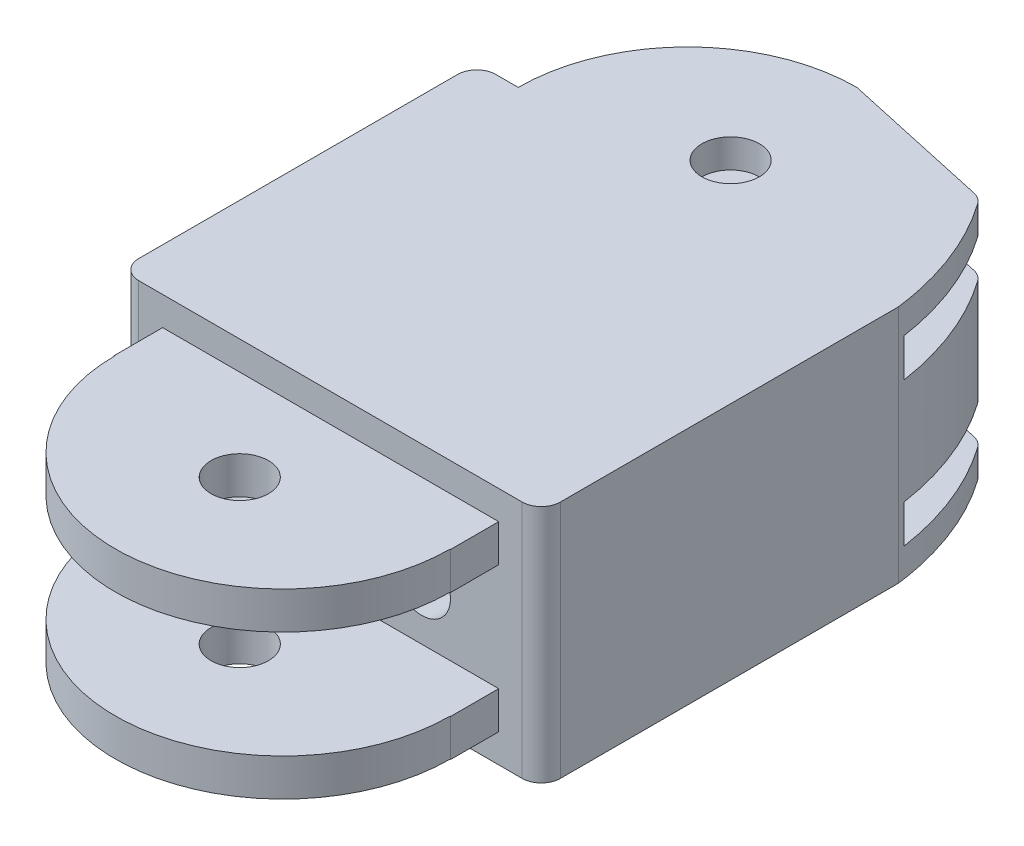
SolidWorks part; units mm, degrees
ref_plane "Front Plane" through (0, 0, 0) normal (0, 0, 1) x (1, 0, 0)
ref_plane "Top Plane" through (0, 0, 0) normal (0, 1, 0) x (1, 0, 0)
ref_plane "Right Plane" through (0, 0, 0) normal (1, 0, 0) x (0, 0, -1)
sketch "Sketch2" plane through (0, 0, 0) normal (0, 0, 1) x (1, 0, 0)
  line L0 (-24.2561, -24.0702) -> (-22.0061, -24.0702) construction
  line L1 (-24.2561, -17.8202) -> (-2.2017, -17.8202) construction
  line L2 (-24.2561, -17.8202) -> (-24.2561, -30.3202) construction
  line L3 (-24.2561, -30.3202) -> (-2.2017, -30.3202) construction
  line L4 (-2.2017, -17.8202) -> (-2.2017, -30.3202) construction
  line L5 (-2.2017, -24.0702) -> (-4.4517, -24.0702) construction
  line L6 (-22.0061, -24.0702) -> (-22.0061, -30.3202) construction
  line L7 (-4.4517, -24.0702) -> (-4.4517, -30.3202) construction
  line L8 (-24.2561, -17.8202) -> (-24.2561, -19.3148) construction
  line L9 (-24.2561, -19.3148) -> (-22.0061, -19.3148) construction
  line L10 (-2.2017, -17.8202) -> (-2.2017, -19.3148) construction
  line L11 (-2.2017, -19.3148) -> (-4.4517, -19.3148) construction
  line L12 (-2.2017, -30.3202) -> (-2.2017, -28.8202) construction
  line L13 (-2.2017, -28.8202) -> (-4.4517, -28.8202) construction
  line L14 (-24.2561, -30.3202) -> (-24.2561, -28.8202) construction
  line L15 (-24.2561, -28.8202) -> (-22.0061, -28.8202) construction
  line L17 (-22.0061, -28.8202) -> (-4.4517, -28.8202)
  line L18 (-22.0061, -28.8202) -> (-22.0061, -26.8702)
  line L19 (-22.0061, -26.8702) -> (-4.4517, -26.8702)
  line L20 (-4.4517, -28.8202) -> (-4.4517, -26.8702)
  line L21 (-22.0061, -28.8202) -> (-4.4517, -26.8702) construction
  line L22 (-22.0061, -26.8702) -> (-4.4517, -28.8202) construction
  line L23 (-22.0061, -19.3148) -> (-4.4517, -19.3148)
  line L24 (-22.0061, -19.3148) -> (-22.0061, -21.2648)
  line L25 (-22.0061, -21.2648) -> (-4.4517, -21.2648)
  line L26 (-4.4517, -19.3148) -> (-4.4517, -21.2648)
  line L27 (-22.0061, -19.3148) -> (-4.4517, -21.2648) construction
  line L28 (-22.0061, -21.2648) -> (-4.4517, -19.3148) construction
  point P19 (-13.2289, -27.8452)
  point P22 (-13.2289, -20.2898)
extrude "Boss-Extrude1" add sketch "Sketch2" along normal blind 8.75
sketch "Sketch3" plane through (0, -19.3148, 0) normal (0, 1, 0) x (1, 0, 0)
  line L0 (-4.4517, 0) -> (-22.0061, 0) construction
  line L1 (-4.4517, -8.75) -> (-22.0061, -8.75) construction
  arc A0 (-13.2289, -8.75) -> (-4.4789, 0) centre (-13.2289, 0) ccw
  arc A1 (-13.2289, -8.75) -> (-21.9789, 0) centre (-13.2289, 0) cw
  spline S0 degree 2 poles (-22.0061, -8.75) (-13.2289, -12.4735) (-4.4517, -8.75) knots 0 0 0 1 1 1
  spline S1 degree 2 poles (-21.9789, 0) (-25.927, -4.2429) (-22.0061, -8.75) knots 0 0 0 1 1 1
  spline S2 degree 2 poles (-4.4789, 0) (1.1383, -4.1517) (-4.4517, -8.75) knots 0 0 0 1 1 1
extrude "Cut-Extrude1" cut sketch "Sketch3" against normal through all contours S0 S2 A0 A1 S1
sketch "Sketch4" plane through (0, 0, 0) normal (0, 0, -1) x (-1, 0, 0)
  line L0 (22.0061, -19.3148) -> (24.2561, -19.3148) construction
  line L1 (22.0061, -19.3148) -> (4.4789, -19.3148) construction
  line L2 (22.0061, -19.3148) -> (22.0061, -28.8202) construction
  line L3 (22.0061, -28.8202) -> (4.4789, -28.8202) construction
  line L4 (4.4789, -19.3148) -> (4.4789, -28.8202) construction
  line L5 (22.0061, -19.3148) -> (4.4789, -28.8202) construction
  line L6 (22.0061, -28.8202) -> (4.4789, -19.3148) construction
  line L7 (24.2561, -19.3148) -> (24.2561, -17.8148) construction
  line L8 (4.4789, -28.8202) -> (2.2289, -28.8202) construction
  line L9 (2.2289, -28.8202) -> (2.2289, -30.3202) construction
  line L11 (24.2561, -17.8148) -> (2.2289, -17.8148)
  line L12 (24.2561, -17.8148) -> (24.2561, -30.3202)
  line L13 (24.2561, -30.3202) -> (2.2289, -30.3202)
  line L14 (2.2289, -17.8148) -> (2.2289, -30.3202)
  line L15 (24.2561, -17.8148) -> (2.2289, -30.3202) construction
  line L16 (24.2561, -30.3202) -> (2.2289, -17.8148) construction
  point P4 (13.2425, -24.0675)
  point P7 (0, 0)
  point P14 (13.2425, -24.0675)
  point P15 (0, 0)
  point P16 (0, 0)
  point P17 (0, 0)
  point P18 (0, 0)
extrude "Boss-Extrude2" add sketch "Sketch4" along normal blind 30 contours L12 L13 L14 L11
sketch "Sketch5" plane through (0, -19.3148, 0) normal (0, 1, 0) x (1, 0, 0)
  line L0 (-13.2289, -8.75) -> (-13.2289, -2.25) construction
  arc A0 (-21.9789, 0) -> (-4.4789, 0) centre (-13.2289, 0) ccw construction
  circle A1 centre (-13.2289, -2.25) radius 1.5
extrude "Cut-Extrude2" cut sketch "Sketch5" against normal blind 12 contours A1
sketch "Sketch6" plane through (0, 0, 0) normal (0, 0, 1) x (1, 0, 0)
  line L0 (-24.2561, -30.3202) -> (-2.2289, -30.3202)
  line L1 (-2.2289, -30.3202) -> (-2.2289, -17.8148)
  line L2 (-2.2289, -17.8148) -> (-24.2561, -17.8148)
  line L3 (-24.2561, -17.8148) -> (-24.2561, -30.3202)
  line L4 (-22.0061, -28.8202) -> (-4.4517, -28.8202)
  line L5 (-4.4517, -28.8202) -> (-4.4517, -26.8702)
  line L6 (-4.4517, -28.8202) -> (-4.4517, -26.8702) construction
  line L7 (-4.4517, -26.8702) -> (-22.0061, -26.8702)
  line L8 (-22.0061, -28.8202) -> (-22.0061, -26.8702)
  line L9 (-22.0061, -21.2648) -> (-22.0061, -19.3148)
  line L10 (-22.0061, -19.3148) -> (-4.4517, -19.3148)
  line L11 (-4.4517, -19.3148) -> (-4.4517, -21.2648)
  line L12 (-4.4517, -21.2648) -> (-22.0061, -21.2648)
extrude "Cut-Extrude3" cut sketch "Sketch6" against normal blind 2.5
sketch "Sketch7" plane through (0, -17.8148, 0) normal (0, 1, 0) x (1, 0, 0)
  line L0 (-13.2425, 30) -> (-13.2425, 23.4057) construction
  line L1 (-24.2561, 30) -> (-2.2289, 30) construction
  line L2 (-13.2425, 23.4057) -> (-13.2425, 21.1557) construction
  line L3 (-22.0869, 21.1557) -> (-24.2561, 21.1557)
  line L4 (-24.2561, 30) -> (-24.2561, 2.5) construction
  line L6 (-2.2289, 30) -> (-2.2289, 2.5) construction
  line L7 (-13.2425, 30) -> (-5.0463, 28.2017)
  circle A0 centre (-13.2425, 23.4057) radius 1.5
  arc A1 (-13.2425, 30) -> (-22.0869, 21.1557) centre (-13.2425, 21.1557) ccw
  spline S0 degree 3 poles (-2.2289, 21.1557) (11.4715, 27.1897) (-11.7652, 53.4313) (-37.0079, 21.5236) (-24.2561, 21.1557) knots 0 0 0 0 0.520113 1 1 1 1
  spline S1 degree 2 poles (-5.0463, 28.2017) (-2.7315, 25.0686) (-2.2289, 21.1557) knots 0 0 0 1 1 1
extrude "Cut-Extrude4" cut sketch "Sketch7" against normal blind 13
sketch "Sketch8" plane through (0, 0, -2.5) normal (0, 0, 1) x (1, 0, 0)
  line L0 (-24.2561, -24.0675) -> (-18.0111, -24.0675) construction
  line L1 (-24.2561, -17.8148) -> (-24.2561, -30.3202) construction
  line L2 (-2.2289, -24.0675) -> (-8.474, -24.0675) construction
  line L3 (-2.2289, -30.3202) -> (-2.2289, -17.8148) construction
  line L4 (-4.4517, -21.2648) -> (-4.4517, -24.0675) construction
  line L5 (-4.4517, -24.0675) -> (-8.474, -24.0675) construction
  circle A0 centre (-18.0111, -24.0675) radius 1.5
  circle A1 centre (-8.474, -24.0675) radius 1.5
extrude "Cut-Extrude5" cut sketch "Sketch8" against normal blind 28
fillet "Fillet3" radius 1 4 edges at (-24.2561, -24.0675, -2.5) (-24.2561, -24.0675, -21.1557) (-2.2289, -24.0675, -2.5) (-5.0463, -24.0675, -28.2017)
ref_plane "Plane4" through (0, 0, -32.5) normal (0, 0, 1) x (1, 0, 0)
sketch "Sketch9" plane through (0, 0, -32.5) normal (0, 0, 1) x (1, 0, 0)
  line L0 (-24.2561, -17.8148) -> (-24.2561, -19.3148) construction
  line L1 (-24.2561, -17.8148) -> (-2.2289, -17.8148) construction
  line L2 (-24.2561, -17.8148) -> (-24.2561, -30.3202) construction
  line L3 (-24.2561, -30.3202) -> (-2.2289, -30.3202) construction
  line L4 (-2.2289, -17.8148) -> (-2.2289, -30.3202) construction
  line L5 (-24.2561, -17.8148) -> (-2.2289, -30.3202) construction
  line L6 (-24.2561, -30.3202) -> (-2.2289, -17.8148) construction
  line L7 (-24.2561, -30.3202) -> (-24.2561, -28.8361) construction
  line L8 (-24.2561, -19.3148) -> (-2.2289, -19.3148)
  line L9 (-24.2561, -19.3148) -> (-24.2561, -21.3148)
  line L10 (-24.2561, -21.3148) -> (-2.2289, -21.3148)
  line L11 (-2.2289, -19.3148) -> (-2.2289, -21.3148)
  line L12 (-24.2561, -19.3148) -> (-2.2289, -21.3148) construction
  line L13 (-24.2561, -21.3148) -> (-2.2289, -19.3148) construction
  line L15 (-24.2561, -28.8361) -> (-2.2289, -28.8361)
  line L16 (-24.2561, -28.8361) -> (-24.2561, -26.8361)
  line L17 (-24.2561, -26.8361) -> (-2.2289, -26.8361)
  line L18 (-2.2289, -28.8361) -> (-2.2289, -26.8361)
  line L19 (-24.2561, -28.8361) -> (-2.2289, -26.8361) construction
  line L20 (-24.2561, -26.8361) -> (-2.2289, -28.8361) construction
  point P4 (-13.2425, -24.0675)
  point P8 (-13.2425, -20.3148)
  point P13 (-13.2425, -27.8361)
extrude "Cut-Extrude6" cut sketch "Sketch9" along normal blind 11
